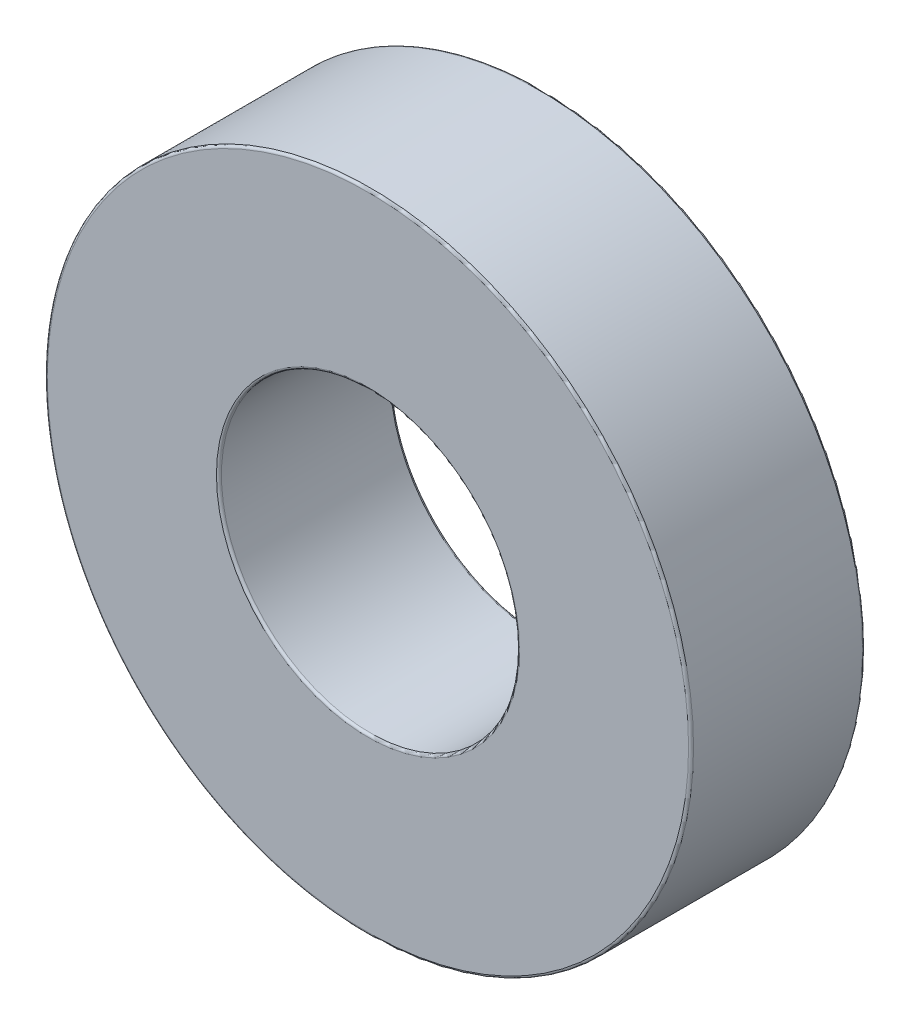
SolidWorks part; units mm, degrees
ref_plane "Front Plane" through (0, 0, 0) normal (0, 0, 1) x (1, 0, 0)
ref_plane "Top Plane" through (0, 0, 0) normal (0, 1, 0) x (1, 0, 0)
ref_plane "Right Plane" through (0, 0, 0) normal (1, 0, 0) x (0, 0, -1)
sketch "Sketch1" plane through (0, 0, 0) normal (0, 0, 1) x (1, 0, 0)
  circle A0 centre (0, 0) radius 6.5
  circle A1 centre (0, 0) radius 3
  dimension "D1" = 13
  dimension "D2" = 6
extrude "Boss-Extrude1" add sketch "Sketch1" along normal blind 3.5
fillet "Fillet1" radius 0.05 4 edges at (6.5, 0, 0) (3, 0, 0) (3, 0, 3.5) (6.5, 0, 3.5)
